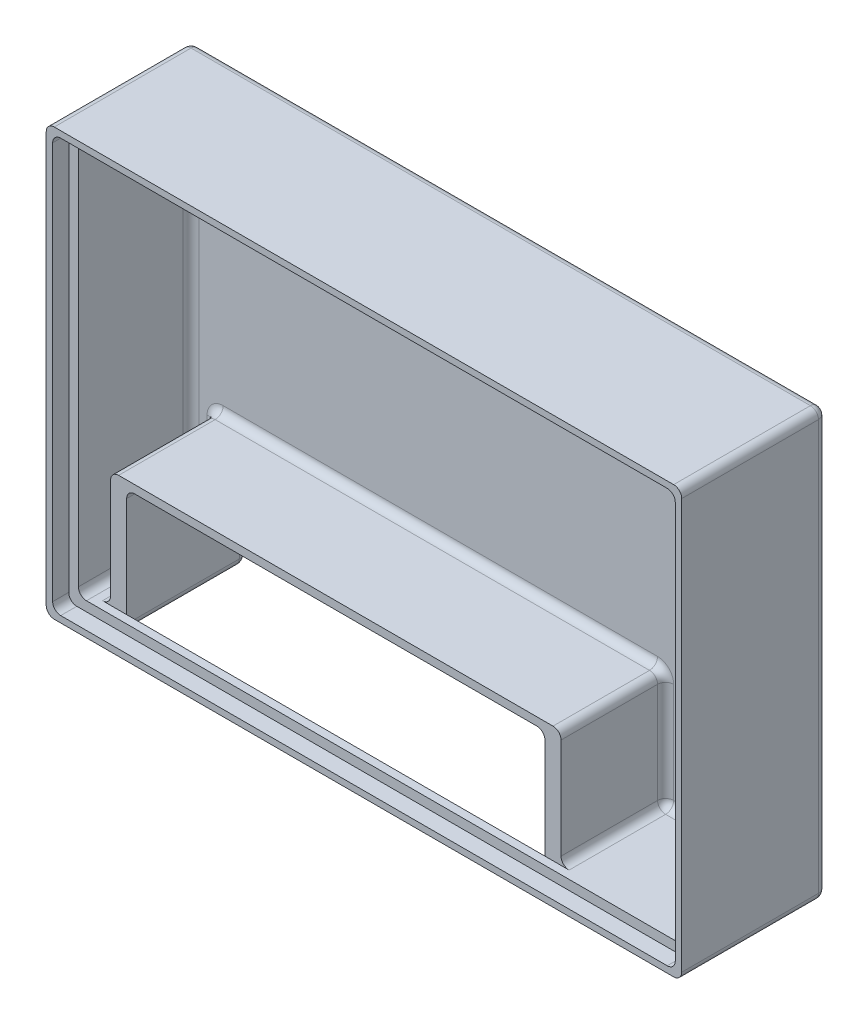
SolidWorks part; units mm, degrees
ref_plane "Front Plane" through (0, 0, 0) normal (0, 0, 1) x (1, 0, 0)
ref_plane "Top Plane" through (0, 0, 0) normal (0, 1, 0) x (1, 0, 0)
ref_plane "Right Plane" through (0, 0, 0) normal (1, 0, 0) x (0, 0, -1)
sketch "Sketch1" plane through (0, 0, 0) normal (0, 0, 1) x (1, 0, 0)
  line L1 (0, 0) -> (79, 0)
  line L2 (0, 0) -> (0, 53)
  line L3 (0, 53) -> (79, 53)
  line L4 (79, 0) -> (79, 53)
  dimension "D1" = 53
  dimension "D2" = 79
extrude "Boss-Extrude1" add sketch "Sketch1" along normal blind 2
sketch "Sketch2" plane through (0, 0, 2) normal (0, 0, 1) x (1, 0, 0)
  line L0 (77, 51) -> (2, 51)
  line L1 (2, 51) -> (2, 2)
  line L2 (2, 2) -> (77, 2)
  line L3 (77, 2) -> (77, 51)
  line L4 (0, 53) -> (0, 0)
  line L5 (0, 0) -> (79, 0)
  line L6 (79, 0) -> (79, 53)
  line L7 (79, 53) -> (0, 53)
  line L8 (0, 53) -> (0, 0)
  line L9 (0, 0) -> (79, 0)
  line L10 (79, 0) -> (79, 53)
  line L11 (79, 53) -> (0, 53)
  dimension "D1" = 0
  dimension "D2" = 2
extrude "Boss-Extrude2" add sketch "Sketch2" along normal blind 14
sketch "Sketch3" plane through (0, 0, 16) normal (0, 0, 1) x (1, 0, 0)
  line L0 (79, 0) -> (79, 53) construction
  line L1 (0, 0) -> (79, 0) construction
  line L2 (0, 53) -> (0, 0) construction
  line L3 (79, 53) -> (0, 53) construction
  line L4 (79, 0) -> (79, 53)
  line L5 (0, 0) -> (79, 0)
  line L6 (0, 53) -> (0, 0)
  line L7 (79, 53) -> (0, 53)
  line L8 (78.2, 52.2) -> (0.8, 52.2)
  line L9 (0.8, 52.2) -> (0.8, 0.8)
  line L10 (0.8, 0.8) -> (78.2, 0.8)
  line L11 (78.2, 0.8) -> (78.2, 52.2)
  dimension "D1" = 0.8
extrude "Boss-Extrude3" add sketch "Sketch3" along normal blind 2
ref_plane "Plane1" through (5, 0, 0) normal (-1, 0, 0) x (0, 0, 1)
sketch "Sketch5" plane through (5, 0, 0) normal (-1, 0, 0) x (0, 0, 1)
  line L0 (0, 53) -> (0, 0) construction
  line L1 (15, 16.5) -> (0, 16.5)
  line L2 (15, 16.5) -> (15, 0)
  line L3 (15, 0) -> (0, 0)
  line L4 (0, 16.5) -> (0, 0)
  line L5 (18, 0) -> (0, 0) construction
  dimension "D1" = 15
  dimension "D2" = 16.5
extrude "Cut-Extrude2" cut sketch "Sketch5" against normal blind 54
sketch "Sketch6" plane through (59, 0, 0) normal (-1, 0, 0) x (0, 0, 1)
  line L0 (15, 0) -> (15, 2) construction
  line L1 (0, 0) -> (15, 0)
  line L2 (0, 0) -> (0, 16.5)
  line L3 (0, 16.5) -> (15, 16.5)
  line L4 (15, 0) -> (15, 16.5)
  line L5 (2, 16.5) -> (0, 16.5) construction
extrude "Boss-Extrude4" add sketch "Sketch6" against normal blind 2
sketch "Sketch7" plane through (0, 16.5, 0) normal (0, -1, 0) x (1, 0, 0)
  line L0 (61, 15) -> (59, 15) construction
  line L1 (59, 0) -> (5, 0)
  line L2 (59, 0) -> (59, 15)
  line L3 (59, 15) -> (5, 15)
  line L4 (5, 0) -> (5, 15)
  line L5 (5, 2) -> (5, 0) construction
extrude "Boss-Extrude6" add sketch "Sketch7" along normal blind 1
sketch "Sketch8" plane through (5, 0, 0) normal (1, 0, 0) x (0, 0, -1)
  line L1 (0, 0) -> (-15, 0)
  line L2 (0, 0) -> (0, 15.5)
  line L3 (0, 15.5) -> (-15, 15.5)
  line L4 (-15, 0) -> (-15, 15.5)
extrude "Boss-Extrude8" add sketch "Sketch8" along normal blind 2
fillet "Fillet1" radius 1 36 edges at (33, 15.5, 0) (59, 7.75, 0) (69, 0, 0) (79, 26.5, 0) (39.5, 53, 0) (0, 26.5, 0) (3.5, 0, 0) (7, 7.75, 0) (59, 0, 7.5) (79, 0, 9) (79, 53, 9) (0, 53, 9) (0, 0, 9) (59, 15.5, 7.5) (7, 15.5, 7.5) (7, 0, 7.5) (2, 51, 9) (5, 16.5, 8.5) (5, 2, 8.5) (2, 2, 9) (77, 51, 9) (77, 2, 9) (0.8, 0.8, 17) (0.8, 52.2, 17) (78.2, 52.2, 17) (78.2, 0.8, 17) (2, 26.5, 2) (39.5, 51, 2) (69, 2, 2) (61, 2, 8.5) (61, 9.25, 2) (61, 16.5, 8.5) (33, 16.5, 2) (5, 9.25, 2) (3.5, 2, 2) (77, 26.5, 2)
